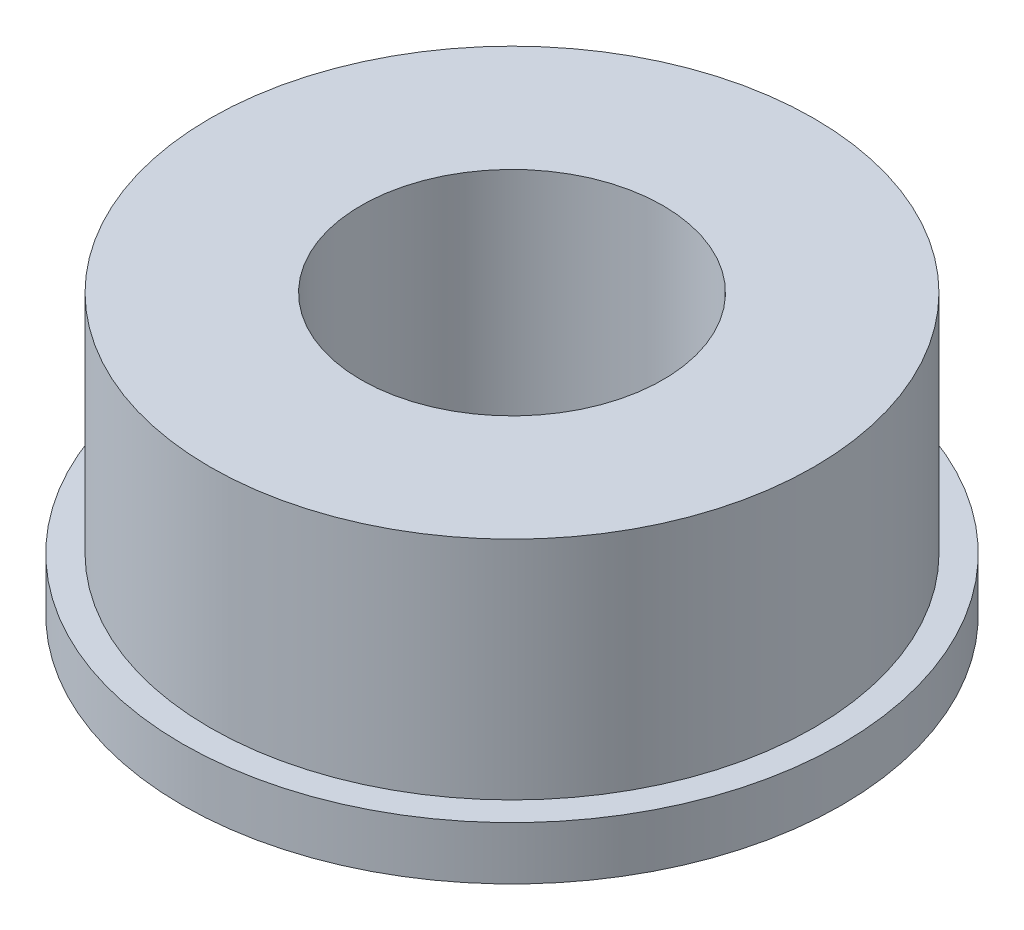
SolidWorks part; units mm, degrees
ref_plane "Front Plane" through (0, 0, 0) normal (0, 0, 1) x (1, 0, 0)
ref_plane "Top Plane" through (0, 0, 0) normal (0, 1, 0) x (1, 0, 0)
ref_plane "Right Plane" through (0, 0, 0) normal (1, 0, 0) x (0, 0, -1)
sketch "Sketch1" plane through (0, 0, 0) normal (0, 1, 0) x (1, 0, 0)
  circle A0 centre (0, 0) radius 6.35
  dimension "D1" = 12.7
extrude "Boss-Extrude1" add sketch "Sketch1" along normal blind 4.7498
sketch "Sketch2" plane through (0, 0, 0) normal (0, -1, 0) x (1, 0, 0)
  circle A0 centre (0, 0) radius 6.9342
  dimension "D1" = 13.8684
extrude "Boss-Extrude2" add sketch "Sketch2" along normal blind 1.1176
sketch "Sketch3" plane through (0, 4.7498, 0) normal (0, 1, 0) x (1, 0, 0)
  circle A0 centre (0, 0) radius 3.175
  dimension "D1" = 6.35
extrude "Cut-Extrude1" cut sketch "Sketch3" against normal up to next
equation "\"OD\"= 0.5in"
equation "\"ID\"= 0.25in"
equation "\"flange_OD\"= 0.546in"
equation "\"main_body_height\"= 0.187in"
equation "\"flange_height\"= 0.044in"
equation "\"D1@Sketch1\"=\"OD\""
equation "\"D1@Boss-Extrude1\"=\"main_body_height\""
equation "\"D1@Sketch2\"=\"flange_OD\""
equation "\"D1@Boss-Extrude2\"=\"flange_height\""
equation "\"D1@Sketch3\"=\"ID\""
